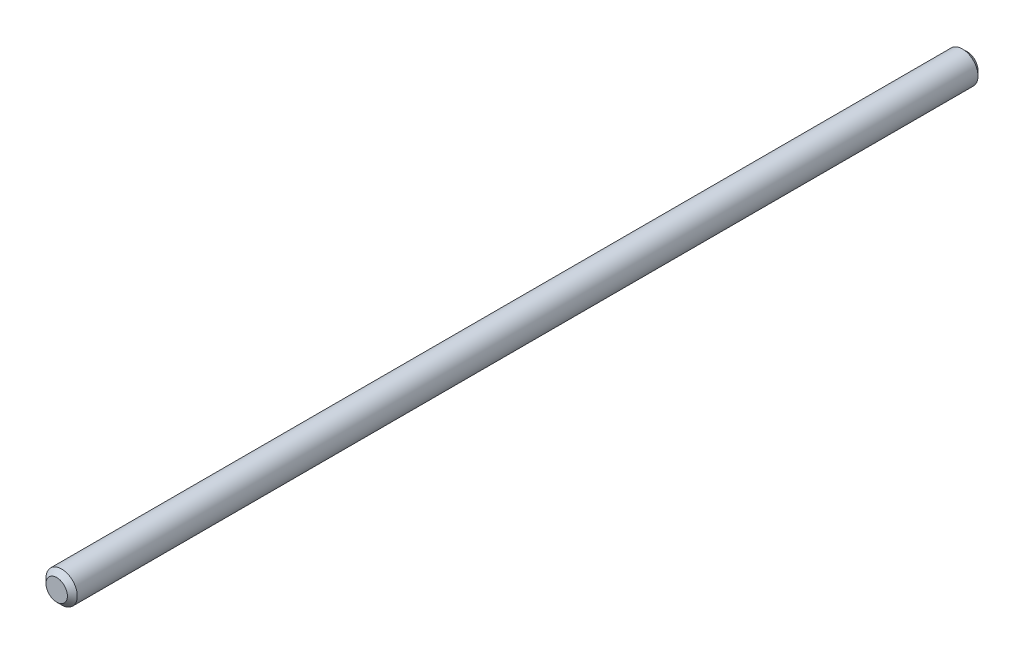
SolidWorks part; units mm, degrees
material "AISI 1020"
ref_plane "Front Plane" through (0, 0, 0) normal (0, 0, 1) x (1, 0, 0)
ref_plane "Top Plane" through (0, 0, 0) normal (0, 1, 0) x (1, 0, 0)
ref_plane "Right Plane" through (0, 0, 0) normal (1, 0, 0) x (0, 0, -1)
sketch "Sketch1" plane through (0, 0, 0) normal (0, 0, 1) x (1, 0, 0)
  circle A0 centre (0, 0) radius 3.175
  dimension "D1" = 6.35
extrude "Boss-Extrude1" add sketch "Sketch1" against normal blind 185
cosmetic thread "Cosmetic Thread1" parameters "D2"=4.8387
chamfer "Chamfer1" distance 1 angle 45 2 edges at (3.175, 0, -185) (3.175, 0, 0)
